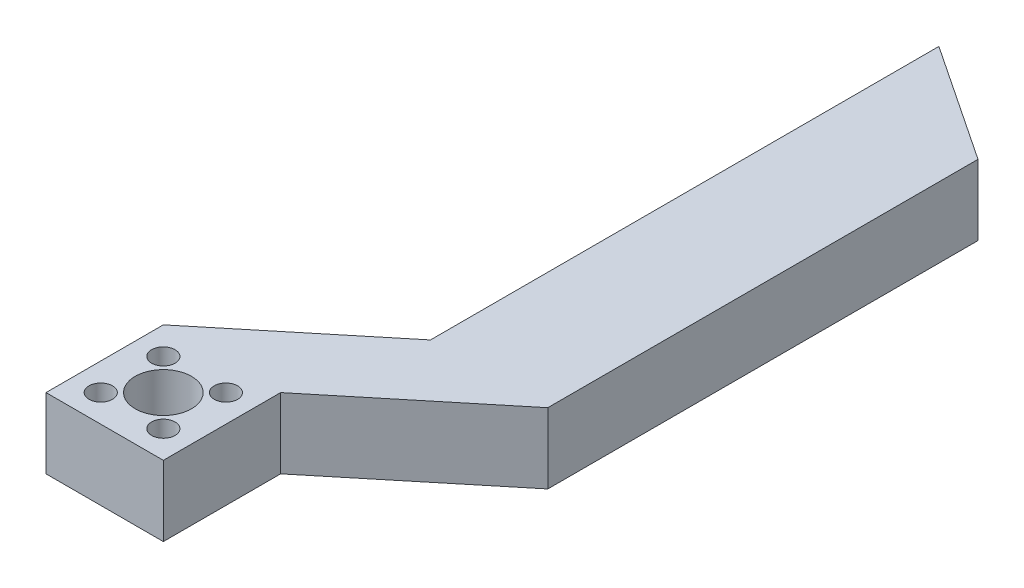
SolidWorks part; units mm, degrees
ref_plane "Alzado" through (0, 0, 0) normal (0, 0, 1) x (1, 0, 0)
ref_plane "Planta" through (0, 0, 0) normal (0, 1, 0) x (1, 0, 0)
ref_plane "Vista lateral" through (0, 0, 0) normal (1, 0, 0) x (0, 0, -1)
sketch "Croquis1" plane through (0, 0, 0) normal (0, 1, 0) x (1, 0, 0)
  line L0 (0, 0) -> (0, 17.1196) construction
  line L1 (7.75, 7.5) -> (26.5, 22.9043)
  line L2 (7.75, -7.5) -> (22.75, -7.5)
  line L3 (7.75, -7.5) -> (7.75, 7.5)
  line L5 (22.75, -7.5) -> (22.75, 7.5)
  line L6 (7.75, -7.5) -> (22.75, 7.5) construction
  line L7 (7.75, 7.5) -> (22.75, -7.5) construction
  line L9 (26.5, 77.9043) -> (26.5, 22.9043)
  line L11 (41.5, 77.9043) -> (41.5, 22.9043)
  line L12 (26.5, 77.9043) -> (41.5, 22.9043) construction
  line L13 (26.5, 22.9043) -> (41.5, 77.9043) construction
  line L16 (22.75, 7.5) -> (41.5, 22.9043)
  line L17 (26.5, 77.9043) -> (26.5, 87.9043)
  line L18 (26.5, 87.9043) -> (41.5, 77.9043)
  circle A0 centre (19.25, 4) radius 1.5
  circle A1 centre (19.25, -4) radius 1.5
  circle A2 centre (11.25, -4) radius 1.5
  circle A3 centre (11.25, 4) radius 1.5
  circle A4 centre (15.25, 0) radius 3.6
  point P3 (15.25, 0)
  point P10 (34, 50.4043)
  point P25 (15.25, 0)
  dimension "D11" = 3
  dimension "D15" = 7.2
  dimension "D1" = 15
  dimension "D2" = 15
  dimension "D3" = 15.25
  dimension "D4" = 26.5
  dimension "D5" = 55
  dimension "D6" = 10
  dimension "D7" = 24.2663
  dimension "D8" = 21.2132
  dimension "D9" = 57.0088
  dimension "D10" = 57.0088
  dimension "D12" = 4
  dimension "D14" = 4
  dimension "D13" = 4
extrude "Saliente-Extruir2" add sketch "Croquis1" along normal blind 9
